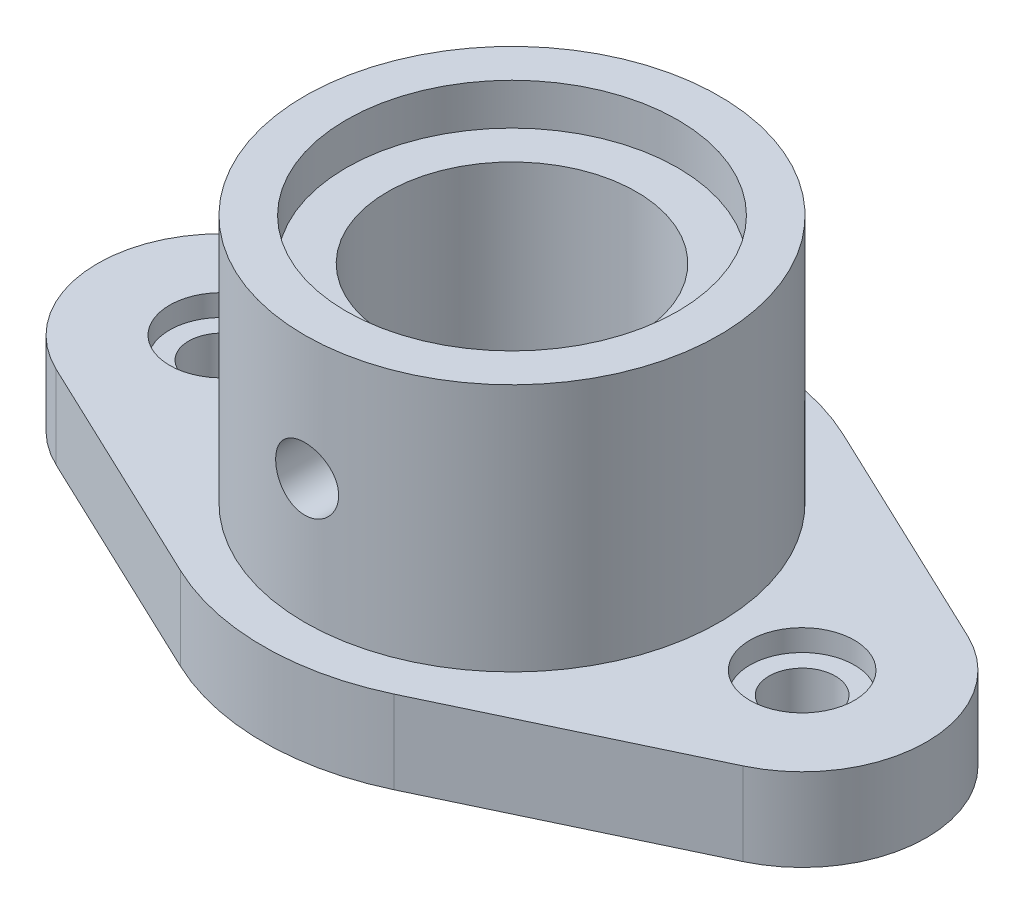
SolidWorks part; units mm, degrees
material "Plain Carbon Steel"
ref_plane "Front Plane" through (0, 0, 0) normal (0, 0, 1) x (1, 0, 0)
ref_plane "Top Plane" through (0, 0, 0) normal (0, 1, 0) x (1, 0, 0)
ref_plane "Right Plane" through (0, 0, 0) normal (1, 0, 0) x (0, 0, -1)
sketch "Sketch1" plane through (0, 0, 0) normal (0, 1, 0) x (1, 0, 0)
  line L0 (-52.6143, 17.2118) -> (-16.3286, 34.4237)
  line L1 (-16.3286, -34.4237) -> (-52.6143, -17.2118)
  line L2 (16.3286, -34.4237) -> (52.6143, -17.2118)
  line L3 (52.6143, 17.2118) -> (16.3286, 34.4237)
  arc A0 (-16.3286, -34.4237) -> (16.3286, -34.4237) centre (0, 0) ccw
  arc A1 (-52.6143, 17.2118) -> (-52.6143, -17.2118) centre (-44.45, 0) ccw
  arc A2 (52.6143, -17.2118) -> (52.6143, 17.2118) centre (44.45, 0) ccw
  arc A3 (16.3286, 34.4237) -> (-16.3286, 34.4237) centre (0, 0) ccw
  dimension "D3" = 76.2
  dimension "D4" = 38.1
  dimension "D5" = 38.1
  dimension "D1" = 44.45
  dimension "D2" = 44.45
extrude "Boss-Extrude1" add sketch "Sketch1" along normal blind 12.7
sketch "Sketch2" plane through (0, 12.7, 0) normal (0, 1, 0) x (1, 0, 0)
  circle A0 centre (0, 0) radius 31.75
  dimension "D1" = 63.5
extrude "Boss-Extrude2" add sketch "Sketch2" along normal blind 38.1
hole_wizard "CBORE for 3/8 Binding Head Machine Screw1" positions "Sketch3" profile "Sketch4" counterbore size "3/8" standard "ANSI Inch" end condition through all
sketch "Sketch3" plane through (0, 50.8, 0) normal (0, 1, 0) x (1, 0, 0)
  point P0 (0, 0)
sketch "Sketch4" plane through (0, 50.8, 0) normal (1, 0, 0) x (0, 0, 1)
  line L0 (0, 0) -> (0, 50.8)
  line L1 (0, 50.8) -> (19.05, 50.8)
  line L3 (19.05, 50.8) -> (19.05, 6.35)
  line L4 (19.05, 6.35) -> (25.4, 6.35)
  line L5 (25.4, 6.35) -> (25.4, 0)
  line L7 (25.4, 0) -> (0, 0)
  line L11 (0, -6.35) -> (0, 107.95) construction
  dimension "Thru Hole Dia." = 38.1
  dimension "Thru Hole Depth" = 50.8
  dimension "C'Bore Dia." = 50.8
  dimension "C'Bore Depth" = 6.35
hole_wizard "CBORE for 3/8 Binding Head Machine Screw2" positions "Sketch5" profile "Sketch6" counterbore size "3/8" standard "ANSI Inch" end condition through all
sketch "Sketch5" plane through (0, 12.7, 0) normal (0, 1, 0) x (1, 0, 0)
  point P0 (-44.45, 0)
  point P3 (44.45, 0)
sketch "Sketch6" plane through (-44.45, 12.7, 0) normal (1, 0, 0) x (0, 0, 1)
  line L0 (0, 0) -> (0, 12.7)
  line L1 (0, 12.7) -> (5.08, 12.7)
  line L3 (5.08, 12.7) -> (5.08, 3.302)
  line L4 (5.08, 3.302) -> (8.001, 3.302)
  line L5 (8.001, 3.302) -> (8.001, 0)
  line L7 (8.001, 0) -> (0, 0)
  line L11 (0, -6.35) -> (0, 107.95) construction
  dimension "Thru Hole Dia." = 10.16
  dimension "Thru Hole Depth" = 12.7
  dimension "C'Bore Dia." = 16.002
  dimension "C'Bore Depth" = 3.302
hole_wizard "3/8 (0.38) Diameter Hole1" positions "Sketch8" profile "Sketch9" hole size "3/8" standard "ANSI Inch"
sketch "Sketch8" plane through (0, 0, 0) normal (0, 0, 1) x (1, 0, 0)
  line L0 (-16.3286, 0) -> (16.3286, 0) construction
  point P0 (0, 31.75)
  point P5 (0, 0)
  dimension "D1" = 31.75
sketch "Sketch9" plane through (0, 31.75, 0) normal (1, 0, 0) x (0, 1, 0)
  line L0 (0, 0) -> (0, 38.1)
  line L1 (0, 38.1) -> (4.826, 38.1)
  line L2 (4.826, 38.1) -> (4.826, 0)
  line L5 (4.826, 0) -> (0, 0)
  line L11 (0, -6.35) -> (0, 107.95) construction
  dimension "Thru Hole Dia." = 9.652
  dimension "Thru Hole Depth" = 38.1
